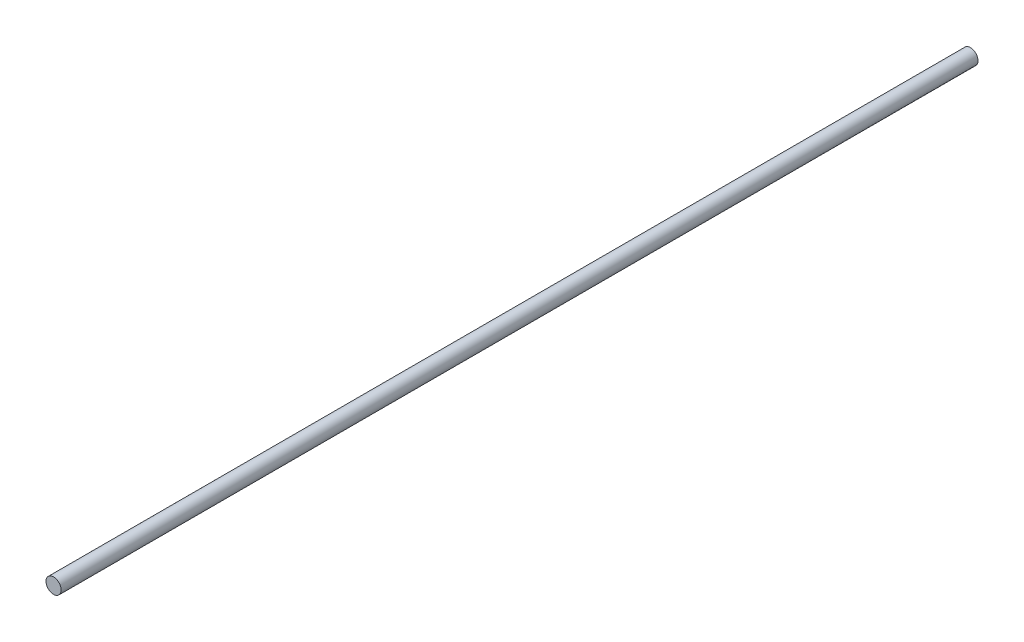
SolidWorks part; units mm, degrees
ref_plane "前视基准面" through (0, 0, 0) normal (0, 0, 1) x (1, 0, 0)
ref_plane "上视基准面" through (0, 0, 0) normal (0, 1, 0) x (1, 0, 0)
ref_plane "右视基准面" through (0, 0, 0) normal (1, 0, 0) x (0, 0, -1)
sketch "草图1" plane through (0, 0, 0) normal (0, 0, 1) x (1, 0, 0)
  circle A0 centre (-9.7143, 12.0214) radius 4
extrude "凸台-拉伸1" add sketch "草图1" along normal blind 484
